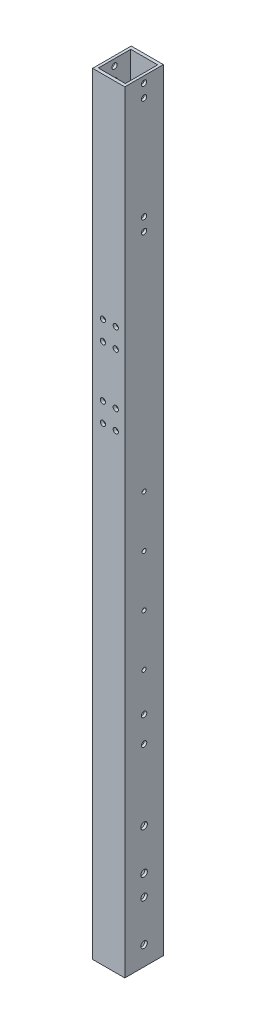
SolidWorks part; units mm, degrees
material "6061 合金"
ref_plane "前视基准面" through (0, 0, 0) normal (0, 0, 1) x (1, 0, 0)
ref_plane "上视基准面" through (0, 0, 0) normal (0, 1, 0) x (1, 0, 0)
ref_plane "右视基准面" through (0, 0, 0) normal (1, 0, 0) x (0, 0, -1)
sketch "草图1" plane through (0, 0, 0) normal (0, 1, 0) x (1, 0, 0)
  line L5 (-12.5, 15) -> (12.5, 15)
  line L6 (-12.5, 15) -> (-12.5, -15)
  line L11 (-12.5, -15) -> (12.5, -15)
  line L12 (12.5, 15) -> (12.5, -15)
  line L13 (-12.5, 15) -> (12.5, -15) construction
  line L14 (-12.5, -15) -> (12.5, 15) construction
  line L15 (-10.5, 12.6) -> (10.5, 12.6)
  line L16 (-10.5, 12.6) -> (-10.5, -12.6)
  line L17 (-10.5, -12.6) -> (10.5, -12.6)
  line L18 (10.5, 12.6) -> (10.5, -12.6)
  line L19 (-10.5, 12.6) -> (10.5, -12.6) construction
  line L20 (-10.5, -12.6) -> (10.5, 12.6) construction
  point P0 (0, 0)
  point P6 (0, 0)
  dimension "D2" = 2
  dimension "D3" = 30
  dimension "2" = 25
extrude "凸台-拉伸1" add sketch "草图1" along normal blind 600
sketch "草图3" plane through (-12.5, 0, 0) normal (-1, 0, 0) x (0, 0, 1)
  line L0 (-15, 600) -> (15, 600) construction
  line L1 (-15, 0) -> (15, 0) construction
  line L2 (0, 600) -> (0, 561.696) construction
  circle A0 centre (0, 595) radius 2.05
  circle A1 centre (0, 585) radius 2.05
  circle A2 centre (0, 505) radius 2.05
  circle A3 centre (0, 495) radius 2.05
  circle A4 centre (0, 15) radius 2.55
  circle A5 centre (0, 47) radius 2.55
  dimension "D1" = 4.1
  dimension "D5" = 5.1
  dimension "D8" = 80
  dimension "D2" = 10
  dimension "D3" = 5
  dimension "D6" = 32
  dimension "D7" = 15
  dimension "D4" = 2
extrude "切除-拉伸2" cut sketch "草图3" against normal through all
sketch "草图4" plane through (0, 0, 15) normal (0, 0, 1) x (1, 0, 0)
  line L1 (12.5, 600) -> (-12.5, 600) construction
  line L2 (-12.5, 400) -> (2.4514, 400) construction
  line L3 (-12.5, 600) -> (-12.5, 0) construction
  line L4 (-12.5, 600) -> (-12.5, 0) construction
  circle A0 centre (5.5, 435) radius 2.05
  circle A1 centre (-4.5, 435) radius 2.05
  circle A2 centre (-4.5, 420) radius 2.05
  circle A3 centre (5.5, 420) radius 2.05
  circle A4 centre (-4.5, 380) radius 2.05
  circle A5 centre (-4.5, 365) radius 2.05
  circle A6 centre (5.5, 365) radius 2.05
  circle A7 centre (5.5, 380) radius 2.05
  dimension "D2" = 4.1
  dimension "D1" = 165
  dimension "D3" = 10
  dimension "D5" = 20
  dimension "D7" = 8
  dimension "D6" = 2
  dimension "D4" = 2
extrude "切除-拉伸3" cut sketch "草图4" against normal through all
sketch "草图6" plane through (-12.5, 0, 0) normal (-1, 0, 0) x (0, 0, 1)
  circle A0 centre (0, 63) radius 2.55
  circle A1 centre (0, 95) radius 2.55
  dimension "D1" = 5.1
  dimension "D2" = 5.1
extrude "切除-拉伸4" cut sketch "草图6" against normal blind 42
sketch "草图7" plane through (12.5, 0, 0) normal (1, 0, 0) x (0, 0, -1)
  circle A0 centre (0, 150) radius 2.1 construction
  circle A1 centre (0, 170) radius 2.1 construction
  circle A2 centre (0, 150) radius 2.1
  circle A3 centre (0, 170) radius 2.1
extrude "切除-拉伸5" cut sketch "草图7" against normal up to next
sketch "草图8" plane through (-12.5, 0, 0) normal (-1, 0, 0) x (0, 0, 1)
  line L0 (0, 175) -> (0, 145) construction
  line L1 (5, 175) -> (5, 145)
  line L2 (-5, 175) -> (-5, 145)
  line L4 (-15, 0) -> (15, 0)
  line L5 (15, 0) -> (15, 600)
  line L6 (15, 600) -> (-15, 600)
  line L7 (-15, 600) -> (-15, 0)
  line L8 (-15, 0) -> (15, 0)
  line L9 (15, 0) -> (15, 600)
  line L10 (15, 600) -> (-15, 600)
  line L11 (-15, 600) -> (-15, 0)
  circle A0 centre (0, 150) radius 2.1 construction
  arc A4 (5, 175) -> (-5, 175) centre (0, 175) ccw
  arc A5 (-5, 145) -> (5, 145) centre (0, 145) ccw
  point P13 (0, 160)
  dimension "D3" = 5
  dimension "D2" = 30
  dimension "D4" = 160
  dimension "D1" = 0
extrude "切除-拉伸8" cut sketch "草图8" against normal blind 5 flip side to cut
sketch "草图9" plane through (-12.5, 0, 0) normal (-1, 0, 0) x (0, 0, 1)
  line L0 (-15, 600) -> (15, 600) construction
  line L1 (15, 600) -> (15, 0) construction
  circle A0 centre (0, 320) radius 1.6
  circle A1 centre (0, 280) radius 1.6
  circle A2 centre (0, 240) radius 1.6
  circle A3 centre (0, 200) radius 1.6
  dimension "D1" = 3.2
  dimension "D2" = 280
  dimension "D3" = 15
  dimension "D5" = 40
  dimension "D4" = 4
extrude "切除-拉伸9" cut sketch "草图9" against normal blind 40
